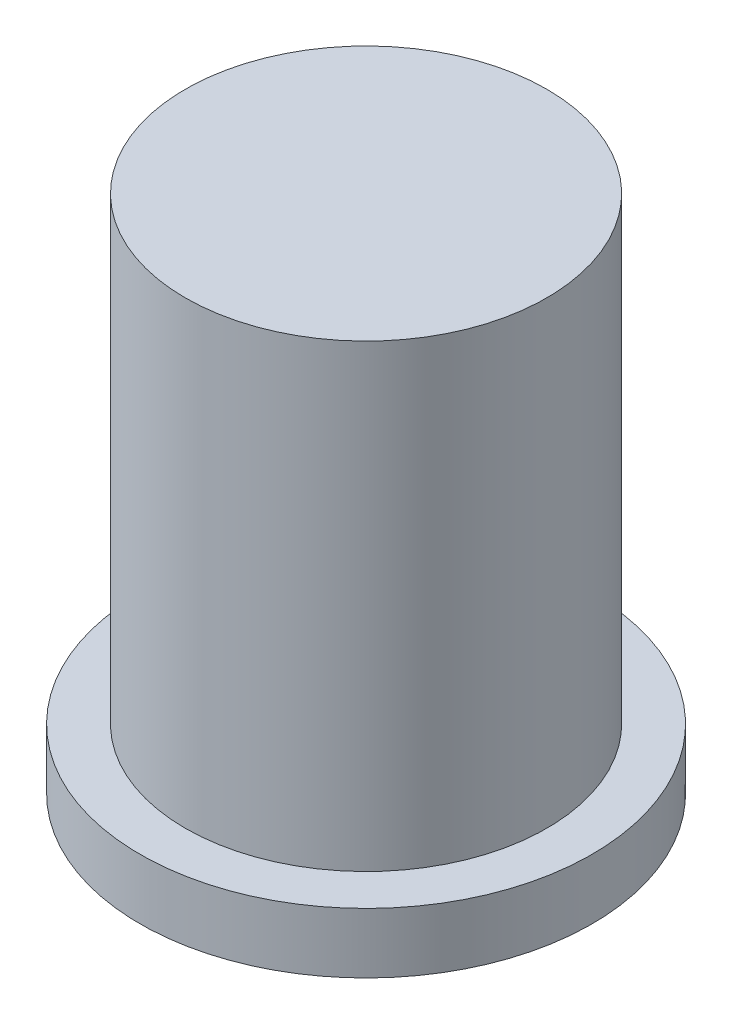
SolidWorks part; units mm, degrees
ref_plane "Front Plane" through (0, 0, 0) normal (0, 0, 1) x (1, 0, 0)
ref_plane "Top Plane" through (0, 0, 0) normal (0, 1, 0) x (1, 0, 0)
ref_plane "Right Plane" through (0, 0, 0) normal (1, 0, 0) x (0, 0, -1)
sketch "Sketch2" plane through (0, 0, 0) normal (0, 1, 0) x (1, 0, 0)
  circle A0 centre (0, 0) radius 1.2
  dimension "D1" = 2.4
extrude "Boss-Extrude1" add sketch "Sketch2" along normal blind 3.45
sketch "Sketch5" plane through (0, 0, 0) normal (0, -1, 0) x (1, 0, 0)
  circle A0 centre (0, 0) radius 1.5
  dimension "D1" = 3
extrude "Boss-Extrude2" add sketch "Sketch5" against normal blind 0.4
